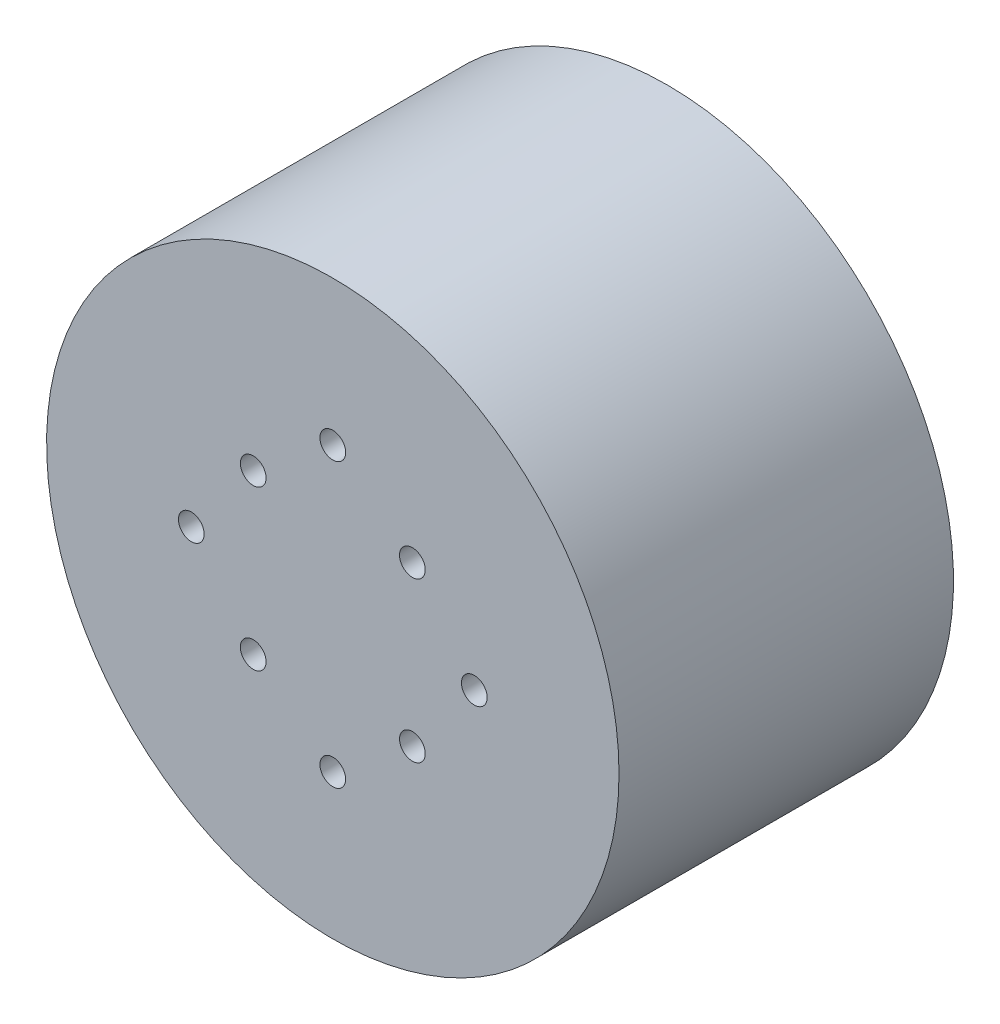
SolidWorks part; units mm, degrees
ref_plane "前视基准面" through (0, 0, 0) normal (0, 0, 1) x (1, 0, 0)
ref_plane "上视基准面" through (0, 0, 0) normal (0, 1, 0) x (1, 0, 0)
ref_plane "右视基准面" through (0, 0, 0) normal (1, 0, 0) x (0, 0, -1)
sketch "草图1" plane through (0, 0, 0) normal (0, 0, 1) x (1, 0, 0)
  circle A0 centre (0, 0) radius 44.5
  dimension "D1" = 89
extrude "凸台-拉伸1" add sketch "草图1" along normal blind 52
sketch "草图2" plane through (0, 0, 0) normal (0, 0, -1) x (-1, 0, 0)
  line L1 (-15, 15) -> (15, 15)
  line L2 (-15, 15) -> (-15, -15)
  line L3 (-15, -15) -> (15, -15)
  line L4 (15, 15) -> (15, -15)
  dimension "D1" = 30
  dimension "D2" = 15
  dimension "D3" = 15
hole_wizard "M4 螺纹孔的螺纹孔钻头1" positions "3D草图1" profile "草图3" hole size "M4" standard "GB"
sketch3d "3D草图1"
  point P0 (15, 15, 0)
  point P3 (-15, 15, 0)
  point P6 (-15, -15, 0)
  point P9 (15, -15, 0)
sketch "草图3" plane through (15, 15, 0) normal (1, 0, 0) x (0, 1, 0)
  line L0 (0, 0) -> (0, 12.9914)
  line L1 (0, 12.9914) -> (1.65, 12)
  line L2 (1.65, 12) -> (1.65, 0)
  line L5 (1.65, 0) -> (0, 0)
  line L10 (0, 12.9914) -> (-1.65, 12) construction
  line L11 (0, -6.35) -> (0, 107.95) construction
  dimension "孔直径" = 3.3
  dimension "孔深度" = 12
  dimension "导头角度" = 118
sketch "草图4" plane through (0, 0, 52) normal (0, 0, 1) x (1, 0, 0)
  line L0 (0, 0) -> (0, 20) construction
  line L1 (0, 0) -> (12.3744, 12.3744) construction
  circle A0 centre (0, 0) radius 22 construction
  circle A1 centre (0, 22) radius 2
  circle A2 centre (0, 0) radius 17.5 construction
  circle A3 centre (12.3744, 12.3744) radius 2
  dimension "D1" = 44
  dimension "D2" = 35
  dimension "D4" = 4
  dimension "D3" = 45
extrude "切除-拉伸1" cut sketch "草图4" against normal blind 10
pattern_circular "阵列(圆周)1" count 4 every 90 about axis through (0, 0, 0) along (0, 0, 1) of "切除-拉伸1"
sketch "草图5" plane through (0, 0, 0) normal (0, 0, -1) x (-1, 0, 0)
  line L1 (38.5047, -26.0166) -> (57.9829, -26.0166)
  line L2 (38.5047, -26.0166) -> (38.5047, 22.5308)
  line L3 (38.5047, 22.5308) -> (57.9829, 22.5308)
  line L4 (57.9829, -26.0166) -> (57.9829, 22.5308)
extrude "切除-拉伸2" cut sketch "草图5" against normal blind 10
sketch "草图6" plane through (-38.5047, 0, 0) normal (-1, 0, 0) x (0, 0, 1)
  line L1 (2.7128, -14.8532) -> (7.9581, -14.8532)
  line L2 (2.7128, -14.8532) -> (2.7128, 14.1993)
  line L3 (2.7128, 14.1993) -> (7.9581, 14.1993)
  line L4 (7.9581, -14.8532) -> (7.9581, 14.1993)
extrude "切除-拉伸3" cut sketch "草图6" against normal blind 10
